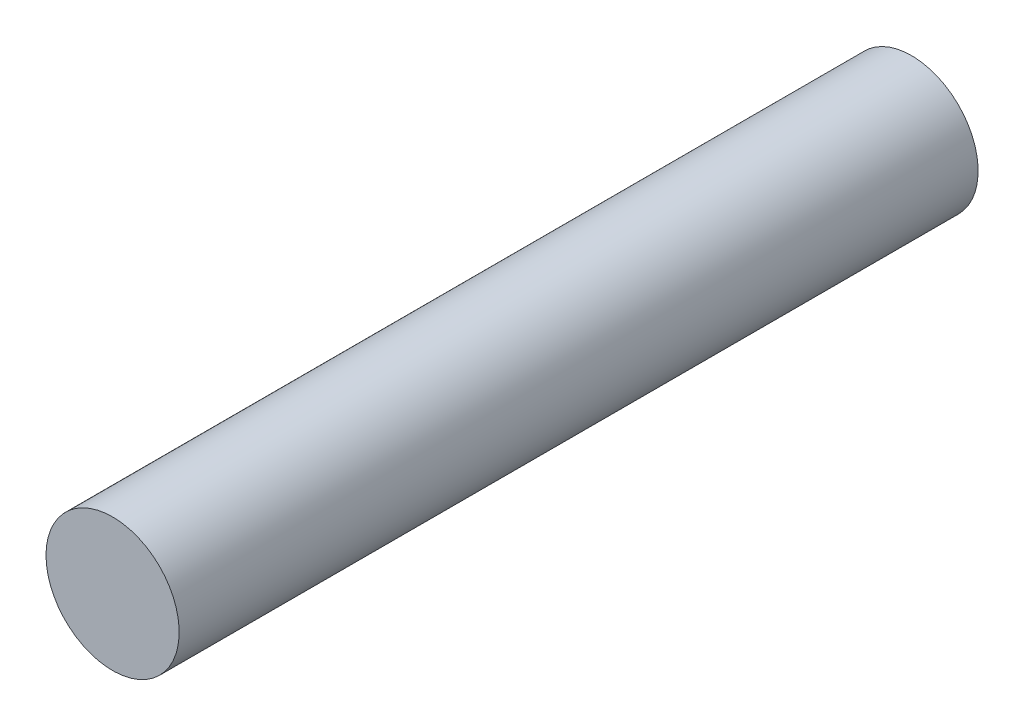
SolidWorks part; units mm, degrees
ref_plane "Front Plane" through (0, 0, 0) normal (0, 0, 1) x (1, 0, 0)
ref_plane "Top Plane" through (0, 0, 0) normal (0, 1, 0) x (1, 0, 0)
ref_plane "Right Plane" through (0, 0, 0) normal (1, 0, 0) x (0, 0, -1)
sketch "Sketch1" plane through (0, 0, 0) normal (0, 0, 1) x (1, 0, 0)
  circle A0 centre (0, 0) radius 12.7
extrude "Boss-Extrude1" add sketch "Sketch1" along normal blind 152.4
